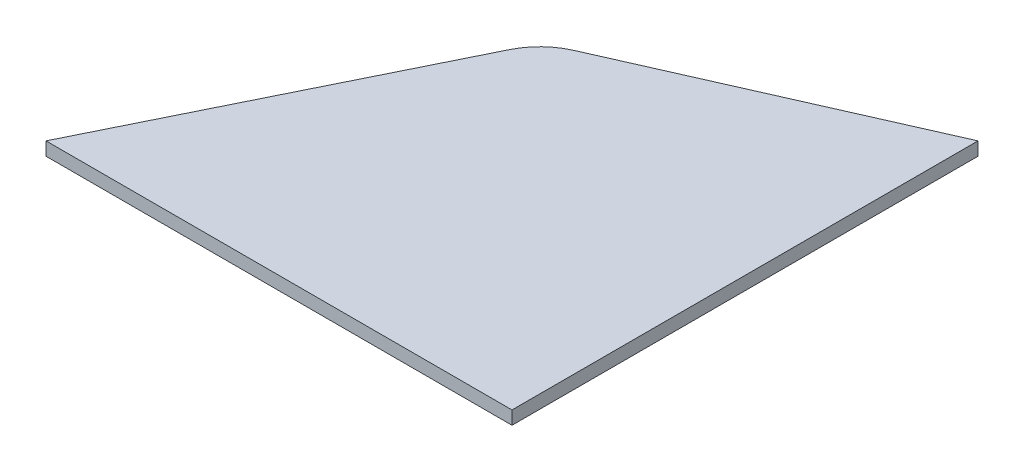
SolidWorks part; units mm, degrees
material "Plástico personalizado"
ref_plane "Plano frontal" through (0, 0, 0) normal (0, 0, 1) x (1, 0, 0)
ref_plane "Plano superior" through (0, 0, 0) normal (0, 1, 0) x (1, 0, 0)
ref_plane "Plano direito" through (0, 0, 0) normal (1, 0, 0) x (0, 0, -1)
sketch "Esboço1" plane through (0, 0, 0) normal (0, 1, 0) x (1, 0, 0)
  line L0 (0, 0) -> (70, 0)
  line L1 (70, 0) -> (70, 70)
  line L2 (70, 70) -> (24.5443, 49.9521)
  line L3 (24.5443, 49.9521) -> (0, 0)
  dimension "D1" = 70
  dimension "D2" = 70
  dimension "D3" = 90
extrude "Ressalto-extrusão1" add sketch "Esboço1" along normal blind 2
fillet "Filete1" radius 10 1 edges at (24.5443, 1, -49.9521)
